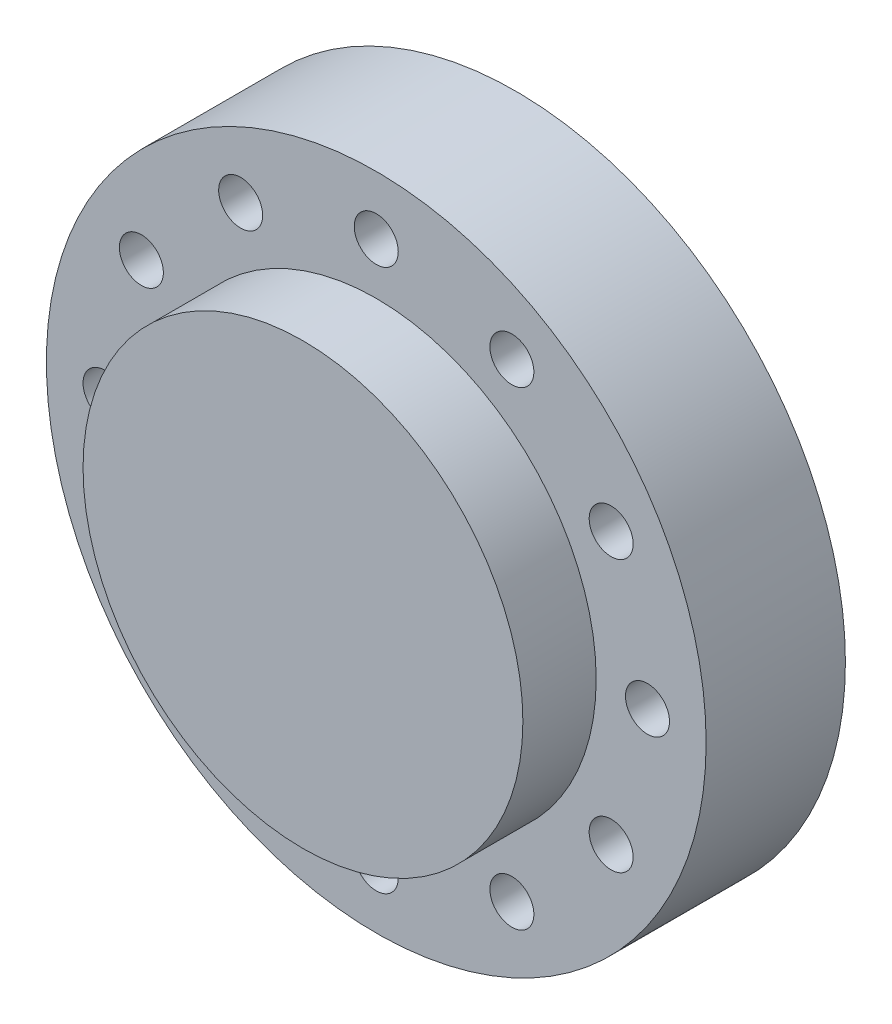
SolidWorks part; units mm, degrees
ref_plane "前视基准面" through (0, 0, 0) normal (0, 0, 1) x (1, 0, 0)
ref_plane "上视基准面" through (0, 0, 0) normal (0, 1, 0) x (1, 0, 0)
ref_plane "右视基准面" through (0, 0, 0) normal (1, 0, 0) x (0, 0, -1)
other "Configuration Table"
sketch "草图1" plane through (0, 0, 0) normal (0, 0, 1) x (1, 0, 0)
  circle A0 centre (0, 0) radius 22.5
  dimension "D1" = 45
extrude "凸台-拉伸1" add sketch "草图1" along normal blind 9.5
sketch "草图2" plane through (0, 0, 9.5) normal (0, 0, 1) x (1, 0, 0)
  circle A0 centre (0, 0) radius 15
  dimension "D1" = 30
extrude "凸台-拉伸2" add sketch "草图2" along normal blind 5
sketch "草图3" plane through (0, 0, 9.5) normal (0, 0, 1) x (1, 0, 0)
  circle A0 centre (0, 0) radius 18.5 construction
  circle A1 centre (0, 18.5) radius 1.5
  dimension "D1" = 37
  dimension "D2" = 3
extrude "切除-拉伸1" cut sketch "草图3" against normal blind 5
sketch "草图5" plane through (0, 0, 9.5) normal (0, 0, 1) x (1, 0, 0)
  circle A0 centre (0, 18.5) radius 1.5
  dimension "D1" = 3
extrude "切除-拉伸2" cut sketch "草图5" against normal through all
sketch "草图9" plane through (0, 0, 0) normal (0, 0, -1) x (-1, 0, 0)
  line L1 (1.2045, 21.4381) -> (-1.9422, 21.0122)
  line L2 (-1.9422, 21.0122) -> (-3.1467, 18.0741)
  line L3 (-3.1467, 18.0741) -> (-1.2045, 15.5619)
  line L4 (-1.2045, 15.5619) -> (1.9422, 15.9878)
  line L5 (1.9422, 15.9878) -> (3.1467, 18.9259)
  line L6 (3.1467, 18.9259) -> (1.2045, 21.4381)
  circle A0 centre (0, 18.5) radius 2.75 construction
  dimension "D1" = 5.5
extrude "切除-拉伸6" cut sketch "草图9" against normal blind 3
pattern_circular "阵列(圆周)1" count 12 over 360 about axis through (0, 0, 0) along (0, 0, 1) of "切除-拉伸1", "切除-拉伸6", "切除-拉伸2"
